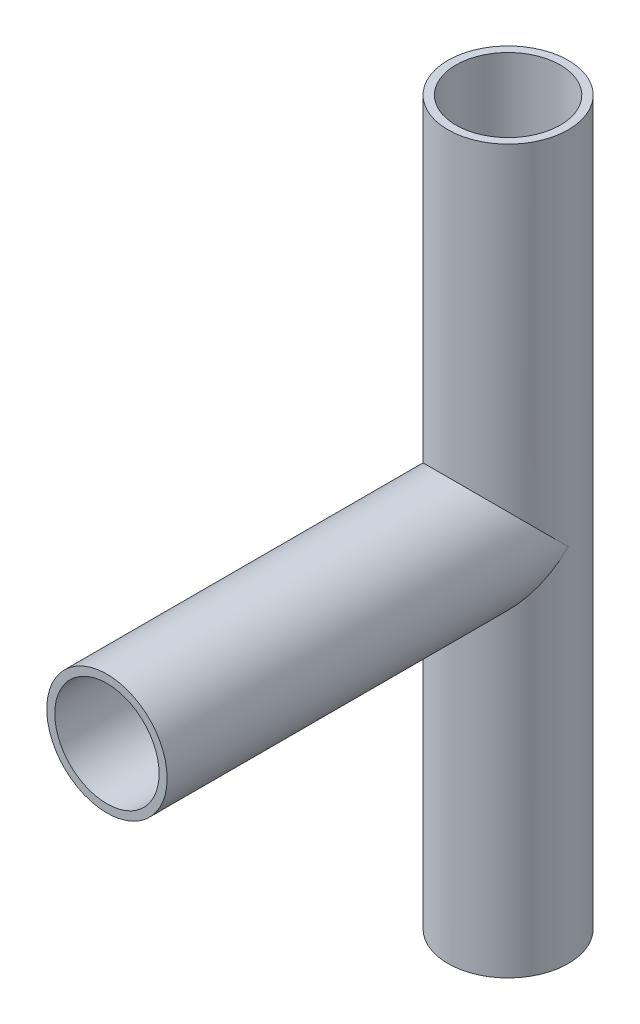
SolidWorks part; units mm, degrees
ref_plane "Front Plane" through (0, 0, 0) normal (0, 0, 1) x (1, 0, 0)
ref_plane "Top Plane" through (0, 0, 0) normal (0, 1, 0) x (1, 0, 0)
ref_plane "Right Plane" through (0, 0, 0) normal (1, 0, 0) x (0, 0, -1)
sketch "Sketch1" plane through (0, 0, 0) normal (0, 0, 1) x (1, 0, 0)
  circle A0 centre (0, 0) radius 13
  circle A1 centre (0, 0) radius 15
  dimension "D1" = 26
  dimension "D2" = 30
extrude "Boss-Extrude1" add sketch "Sketch1" along normal blind 100
sketch "Sketch2" plane through (0, 0, 0) normal (0, 1, 0) x (1, 0, 0)
  circle A0 centre (0, 0) radius 15
extrude "Cut-Extrude1" cut sketch "Sketch2" against normal blind 100
sketch "Sketch3" plane through (0, 0, 0) normal (0, 1, 0) x (1, 0, 0)
  circle A0 centre (0, 0) radius 15
extrude "Cut-Extrude4" cut sketch "Sketch3" against normal through all both and the other way through all
sketch "Sketch4" plane through (0, 0, 0) normal (0, 1, 0) x (1, 0, 0)
  circle A0 centre (0, 0) radius 13
  circle A1 centre (0, 0) radius 15
  dimension "D1" = 26
  dimension "D2" = 30
extrude "Boss-Extrude3" add sketch "Sketch4" along normal blind 90
sketch "Sketch6" plane through (0, 0, 0) normal (0, -1, 0) x (1, 0, 0)
  circle A0 centre (0, 0) radius 13
  circle A1 centre (0, 0) radius 15
extrude "Boss-Extrude4" add sketch "Sketch6" along normal blind 90
